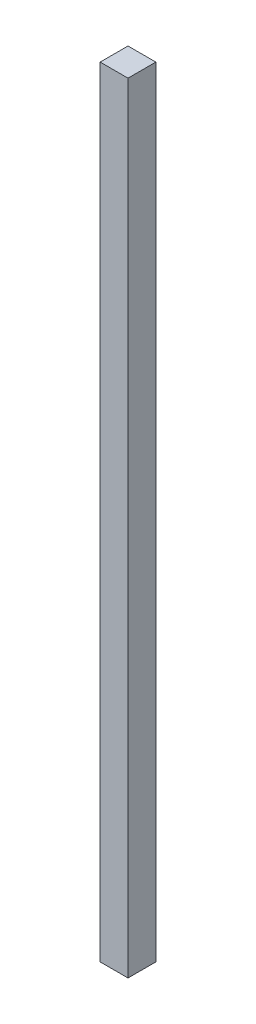
SolidWorks part; units mm, degrees
ref_plane "Front Plane" through (0, 0, 0) normal (0, 0, 1) x (1, 0, 0)
ref_plane "Top Plane" through (0, 0, 0) normal (0, 1, 0) x (1, 0, 0)
ref_plane "Right Plane" through (0, 0, 0) normal (1, 0, 0) x (0, 0, -1)
sketch "Sketch1" plane through (0, 0, 0) normal (0, 1, 0) x (1, 0, 0)
  line L1 (0, 0) -> (-25, 0)
  line L2 (0, 0) -> (0, -25)
  line L3 (0, -25) -> (-25, -25)
  line L4 (-25, 0) -> (-25, -25)
  dimension "D1" = 25
  dimension "D2" = 25
extrude "Boss-Extrude1" add sketch "Sketch1" along normal blind 700
